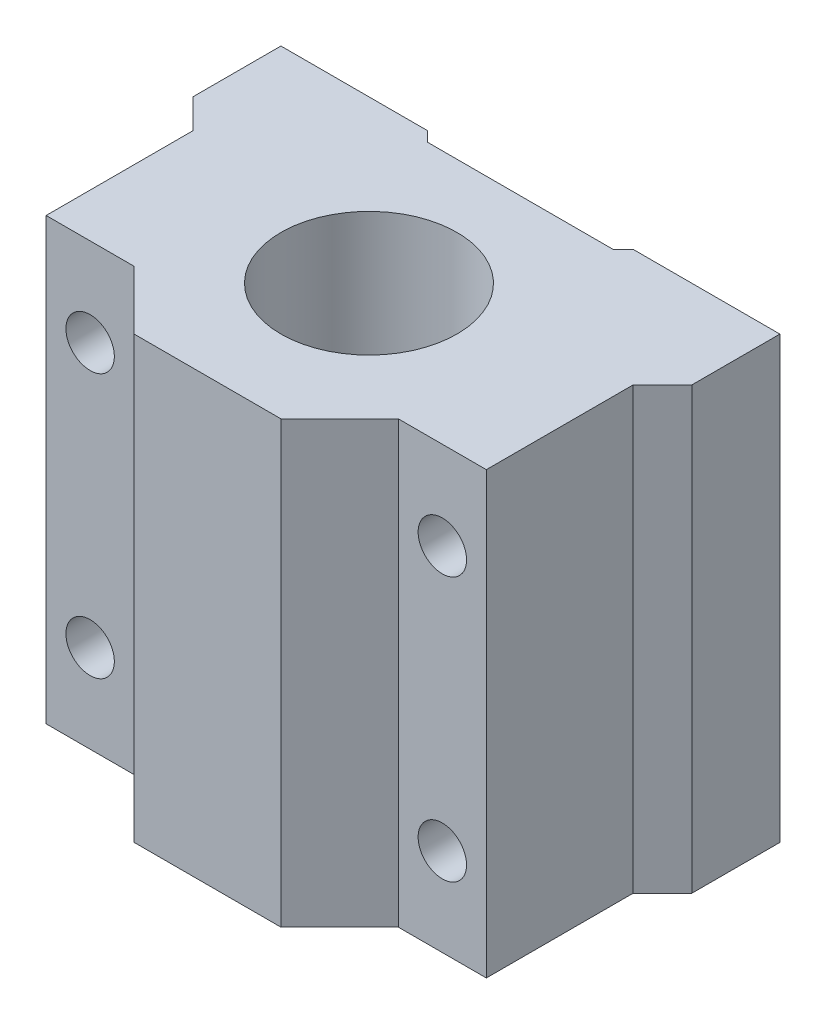
SolidWorks part; units mm, degrees
ref_plane "Front Plane" through (0, 0, 0) normal (0, 0, 1) x (1, 0, 0)
ref_plane "Top Plane" through (0, 0, 0) normal (0, 1, 0) x (1, 0, 0)
ref_plane "Right Plane" through (0, 0, 0) normal (1, 0, 0) x (0, 0, -1)
sketch "Sketch1" plane through (0, 0, 0) normal (0, 1, 0) x (1, 0, 0)
  line L0 (-17, 0) -> (17, 0) construction
  line L5 (17, 0) -> (0, 0) construction
  line L6 (0, -11) -> (0, 11) construction
  line L7 (17, 11) -> (-17, 11)
  line L8 (-17, 11) -> (-17, 5)
  line L9 (-17, 5) -> (-14.9989, 2.9989)
  line L10 (-14.9989, 2.9989) -> (-14.9989, -7.0011)
  line L11 (-14.9989, -7.0011) -> (-8.9989, -7.0011)
  line L12 (-8.9989, -7.0011) -> (-5, -11)
  line L13 (-5, -11) -> (5, -11)
  line L14 (8.9989, -7.0011) -> (5, -11)
  line L15 (14.9989, -7.0011) -> (8.9989, -7.0011)
  line L16 (14.9989, 2.9989) -> (14.9989, -7.0011)
  line L17 (17, 5) -> (14.9989, 2.9989)
  line L18 (17, 11) -> (17, 5)
  circle A0 centre (0, 0) radius 4
  circle A1 centre (0, 0) radius 6
  point P3 (0, 0)
  point P10 (0, 0)
  dimension "D8" = 8
  dimension "D9" = 12
  dimension "D1" = 34
  dimension "D2" = 22
  dimension "D3" = 17
  dimension "D4" = 6
  dimension "D5" = 2.83
  dimension "D6" = 135
  dimension "D7" = 10
  dimension "D10" = 6
extrude "Boss-Extrude1" add sketch "Sketch1" along normal blind 30 contours L18 L7 L8 L9 L10 L11 L12 L13 L14 L15 L16 L17 A1
sketch "Sketch2" plane through (0, 0, -11) normal (0, 0, -1) x (-1, 0, 0)
  line L8 (0, 6) -> (0, 24) construction
  line L9 (-12, 15) -> (12, 15) construction
  circle A4 centre (12, 6) radius 1.65
  circle A5 centre (-12, 6) radius 1.65
  circle A6 centre (12, 24) radius 1.65
  circle A7 centre (-12, 24) radius 1.65
  point P18 (0, 15)
  point P21 (0, 15)
  dimension "D11" = 24
  dimension "D2" = 3.3
  dimension "D12" = 18
extrude "Cut-Extrude1" cut sketch "Sketch2" against normal through all
sketch "Sketch3" plane through (0, 0, 0) normal (0, -1, 0) x (1, 0, 0)
  line L0 (0, -11) -> (0, -7.6094) construction
  line L1 (17, -11) -> (-17, -11) construction
  line L2 (-12, -9.3047) -> (12, -9.3047) construction
  line L4 (-6.3159, -10.3159) -> (6.3159, -10.3159)
  line L5 (7, -11) -> (-7, -11)
  line L6 (7, -11) -> (6.3159, -10.3159)
  line L7 (-7, -11) -> (-6.3159, -10.3159)
  point P8 (0, -9.3047)
  dimension "D1" = 24
  dimension "D3" = 5
extrude "Cut-Extrude2" cut sketch "Sketch3" against normal through all
